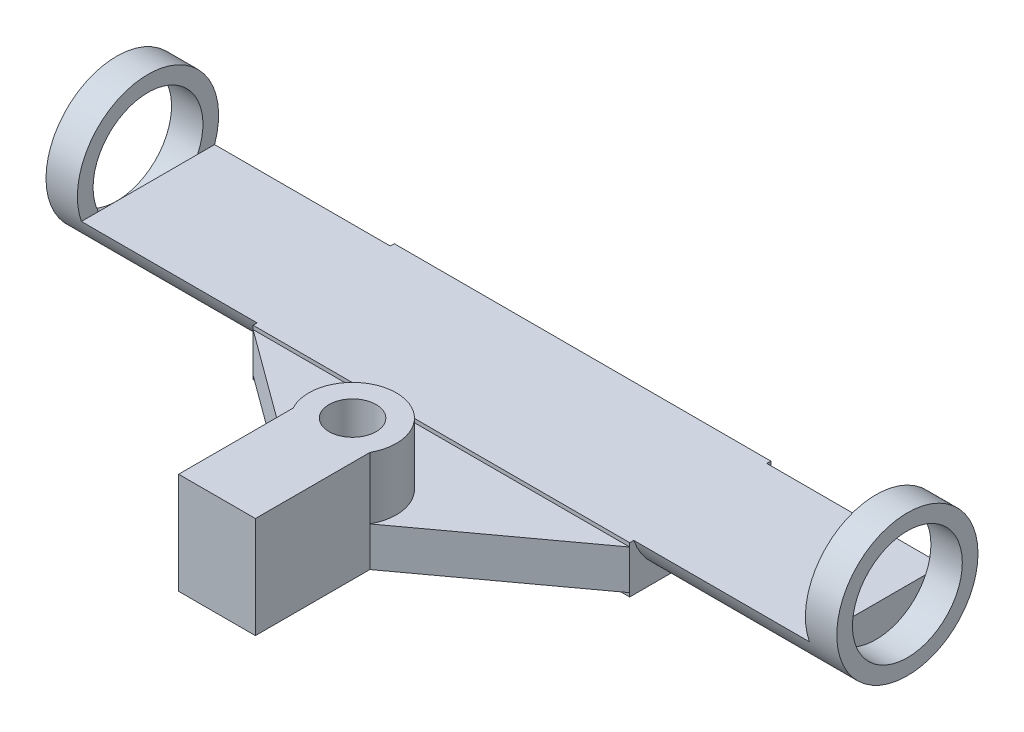
SolidWorks part; units mm, degrees
ref_plane "Front Plane" through (0, 0, 0) normal (0, 0, 1) x (1, 0, 0)
ref_plane "Top Plane" through (0, 0, 0) normal (0, 1, 0) x (1, 0, 0)
ref_plane "Right Plane" through (0, 0, 0) normal (1, 0, 0) x (0, 0, -1)
sketch "Sketch1" plane through (0, 0, 0) normal (0, 1, 0) x (1, 0, 0)
  line L1 (59.2176, -23.8423) -> (-100.7824, -23.8423)
  line L2 (59.2176, -23.8423) -> (59.2176, 4.7327)
  line L3 (59.2176, 4.7327) -> (-100.7824, 4.7327)
  line L4 (-100.7824, -23.8423) -> (-100.7824, 4.7327)
  dimension "D1" = 28.575
  dimension "D2" = 160
extrude "Boss-Extrude1" add sketch "Sketch1" along normal blind 28.575
sketch "Sketch2" plane through (59.2176, 0, 0) normal (1, 0, 0) x (0, 0, -1)
  line L0 (-9.5548, 28.575) -> (-9.5548, 0) construction
  line L1 (-23.8423, 28.575) -> (4.7327, 28.575) construction
  line L2 (-23.8423, 0) -> (4.7327, 0) construction
  line L3 (4.7327, 14.2875) -> (-23.8423, 14.2875) construction
  line L4 (4.7327, 28.575) -> (4.7327, 0) construction
  line L5 (-23.8423, 28.575) -> (-23.8423, 0) construction
  circle A0 centre (-9.5548, 14.2875) radius 14.2875
sketch "Sketch3" plane through (0, 28.575, 0) normal (0, 1, 0) x (1, 0, 0)
  line L0 (59.2176, 4.7327) -> (-100.7824, 4.7327) construction
  line L1 (-94.4324, 4.7327) -> (52.8676, 4.7327)
  line L2 (-94.4324, 4.7327) -> (-94.4324, -23.8423)
  line L3 (-94.4324, -23.8423) -> (52.8676, -23.8423)
  line L4 (52.8676, 4.7327) -> (52.8676, -23.8423)
  line L5 (-100.7824, -23.8423) -> (59.2176, -23.8423) construction
  line L6 (-100.7824, 4.7327) -> (-100.7824, -23.8423) construction
  dimension "D1" = 147.3
  dimension "D2" = 6.35
extrude "Cut-Extrude3" cut sketch "Sketch3" against normal blind 19.05
sketch "Sketch4" plane through (0, 0, 23.8423) normal (0, 0, 1) x (1, 0, 0)
  line L0 (-20.7824, 9.525) -> (-20.7824, 0) construction
  line L1 (-94.4324, 9.525) -> (52.8676, 9.525) construction
  line L2 (-100.7824, 0) -> (59.2176, 0) construction
  line L4 (17.3176, 0.7625) -> (-58.8824, 0.7625)
  line L5 (17.3176, 0.7625) -> (17.3176, 8.7625)
  line L6 (17.3176, 8.7625) -> (-58.8824, 8.7625)
  line L7 (-58.8824, 0.7625) -> (-58.8824, 8.7625)
  line L8 (17.3176, 0.7625) -> (-58.8824, 8.7625) construction
  line L9 (17.3176, 8.7625) -> (-58.8824, 0.7625) construction
  point P6 (-20.7824, 4.7625)
  dimension "D1" = 76.2
  dimension "D2" = 8
extrude "Boss-Extrude2" add sketch "Sketch4" along normal blind 45.4
sketch "Sketch5" plane through (0, 8.7625, 0) normal (0, 1, 0) x (1, 0, 0)
  line L0 (-20.7824, -23.8423) -> (-20.7824, -69.2423) construction
  line L1 (-94.4324, -23.8423) -> (52.8676, -23.8423) construction
  line L2 (17.3176, -69.2423) -> (-58.8824, -69.2423) construction
  line L3 (17.3176, -38.1298) -> (-58.8824, -38.1298) construction
  line L4 (-28.5508, -46.0758) -> (-28.5508, -69.2423)
  line L5 (-28.5508, -69.2423) -> (-28.5508, -46.0758)
  line L6 (-13.0139, -46.0758) -> (-13.0139, -69.2423)
  line L7 (17.3176, -69.2423) -> (17.3176, -23.8423) construction
  line L8 (-58.8824, -69.2423) -> (-58.8824, -23.8423) construction
  line L9 (17.3176, -23.8423) -> (-58.8824, -23.8423) construction
  line L10 (-58.8824, -23.8423) -> (-28.5508, -46.0758)
  line L11 (17.3176, -23.8423) -> (-13.0139, -46.0758)
  line L12 (17.3176, -23.8423) -> (17.3176, -69.2423)
  line L13 (17.3176, -69.2423) -> (-13.0139, -69.2423)
  line L14 (-28.5508, -69.2423) -> (-58.8824, -69.2423)
  line L15 (-58.8824, -69.2423) -> (-58.8824, -23.8423)
  line M2 (-58.8824, -23.8423) -> (-58.8824, -69.2423)
  line M3 (-58.8824, -69.2423) -> (17.3176, -69.2423)
  line M4 (17.3176, -69.2423) -> (17.3176, -23.8423)
  dimension "D1" = 14.2875
extrude "Cut-Extrude8" cut sketch "Sketch5" against normal through all contours L11 L6 M4 M3 | L10 L4 M2 M3
sketch "Sketch9" plane through (0, 8.7625, 0) normal (0, 1, 0) x (1, 0, 0)
  line L0 (-46.4509, -32.9548) -> (4.8861, -32.9548) construction
  line L1 (-58.8824, -23.8423) -> (-28.5508, -46.0758) construction
  line L2 (17.3176, -23.8423) -> (-13.0139, -46.0758) construction
  line L3 (17.3176, -23.8423) -> (-58.8824, -23.8423) construction
  line L4 (-28.5508, -46.0758) -> (-28.5508, -69.2423)
  line L5 (-28.5508, -69.2423) -> (-13.0139, -69.2423)
  line L6 (-13.0139, -69.2423) -> (-13.0139, -46.0758)
  arc A0 (-13.0139, -46.0758) -> (-28.5508, -46.0758) centre (-20.7824, -41.815) ccw
  circle A2 centre (-20.7824, -41.815) radius 4.7625
  dimension "D1" = 9.1125
extrude "Boss-Extrude4" add sketch "Sketch9" along normal blind 12.525
sketch "Sketch10" plane through (0, 8.7625, 0) normal (0, 1, 0) x (1, 0, 0)
  circle A0 centre (-20.7824, -41.815) radius 4.7625
extrude "Cut-Extrude10" cut sketch "Sketch10" against normal through all
extrude "Cut-Extrude11" cut sketch "Sketch2" against normal up to vertex flip side to cut
sketch "Sketch13" plane through (-100.7824, 0, 0) normal (-1, 0, 0) x (0, 0, 1)
  line L0 (9.5548, 28.575) -> (9.5548, 0) construction
  line L1 (-4.7327, 28.575) -> (23.8423, 28.575) construction
  line L2 (-4.7327, 0) -> (23.8423, 0) construction
  line L3 (23.8423, 14.2875) -> (-4.7327, 14.2875) construction
  line L4 (23.8423, 28.575) -> (23.8423, 0) construction
  line L5 (-4.7327, 28.575) -> (-4.7327, 0) construction
  circle A0 centre (9.5548, 14.2875) radius 14.2875
  dimension "D1" = 28.575
extrude "Cut-Extrude13" cut sketch "Sketch13" against normal up to vertex flip side to cut
sketch "Sketch14" plane through (59.2176, 0, 0) normal (1, 0, 0) x (0, 0, -1)
  line L0 (-9.5548, 0) -> (-9.5548, 28.575) construction
  circle A0 centre (-9.5548, 14.2875) radius 14.2875 construction
  circle A1 centre (-9.5548, 14.2875) radius 11.1125
extrude "Cut-Extrude14" cut sketch "Sketch14" against normal up to surface (6.35 mm away) up to face at (52.8676, 19.05, 9.5548)
sketch "Sketch15" plane through (-100.7824, 0, 0) normal (-1, 0, 0) x (0, 0, 1)
  line L0 (9.5548, 28.575) -> (9.5548, 0) construction
  circle A0 centre (9.5548, 14.2875) radius 14.2875 construction
  circle A1 centre (9.5548, 14.2875) radius 11.1125
extrude "Cut-Extrude15" cut sketch "Sketch15" against normal up to surface (6.35 mm away) up to face at (-94.4324, 19.05, 9.5548)
sketch "Sketch16" plane through (-94.4324, 0, 0) normal (-1, 0, 0) x (0, 0, 1)
  line L0 (3.831, 4.7625) -> (18.3105, 4.7625) construction
  line L1 (-0.4854, 9.525) -> (19.595, 9.525) construction
  arc A0 (-0.4854, 9.525) -> (19.595, 9.525) centre (9.5548, 14.2875) ccw construction
  ellipse E0 centre (9.5548, 9.525) end of major axis (-0.4854, 9.525) minor radius 4.7625
  dimension "D1" = 4.7625
